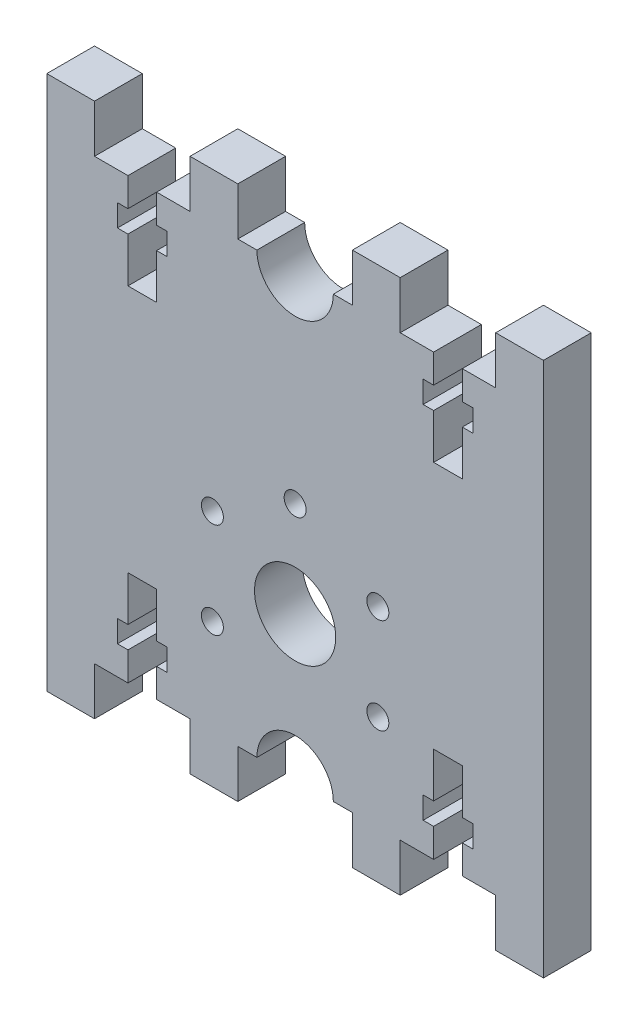
SolidWorks part; units mm, degrees
ref_plane "Front Plane" through (0, 0, 0) normal (0, 0, 1) x (1, 0, 0)
ref_plane "Top Plane" through (0, 0, 0) normal (0, 1, 0) x (1, 0, 0)
ref_plane "Right Plane" through (0, 0, 0) normal (1, 0, 0) x (0, 0, -1)
sketch "Sketch1" plane through (0, 0, 0) normal (0, 0, 1) x (1, 0, 0)
  line L1 (0, 0) -> (20, 0) construction
  line L3 (0, 46) -> (20, 46) construction
  line L8 (10, 46) -> (10, 38.7792) construction
  line L9 (11.5, 46) -> (15, 46)
  line L10 (15, 51) -> (20, 51)
  line L12 (15, 51) -> (15, 46)
  line L13 (8.5, 46) -> (5, 46)
  line L14 (5, 46) -> (5, 51)
  line L15 (5, 51) -> (0, 51)
  line L17 (11.5, 46) -> (8.5, 46) construction
  line L18 (8.5, 46) -> (8.5, 43)
  line L19 (8.5, 40.7) -> (7.4, 40.7)
  line L20 (12.6, 43) -> (12.6, 40.7)
  line L21 (7.4, 43) -> (8.5, 43)
  line L22 (8.5, 40.7) -> (8.5, 36)
  line L23 (8.5, 36) -> (11.5, 36)
  line L24 (11.5, 36) -> (11.5, 40.7)
  line L25 (11.5, 43) -> (12.6, 43)
  line L26 (7.4, 40.7) -> (7.4, 43)
  line L27 (12.6, 40.7) -> (11.5, 40.7)
  line L28 (11.5, 43) -> (11.5, 46)
  line L29 (10, 36) -> (10, 46) construction
  line L30 (10, 0) -> (10, 11.2208) construction
  line L31 (8.5, 0) -> (5, 0)
  line L32 (5, -5) -> (0, -5)
  line L33 (0, -5) -> (0, 0)
  line L34 (5, -5) -> (5, 0)
  line L35 (11.5, 0) -> (15, 0)
  line L36 (15, 0) -> (15, -5)
  line L37 (15, -5) -> (20, -5)
  line L38 (20, -5) -> (20, 0)
  line L39 (8.5, 0) -> (11.5, 0) construction
  line L40 (11.5, 0) -> (11.5, 3)
  line L41 (11.5, 5.3) -> (12.6, 5.3)
  line L42 (7.4, 3) -> (7.4, 5.3)
  line L43 (12.6, 3) -> (11.5, 3)
  line L44 (11.5, 5.3) -> (11.5, 10)
  line L45 (11.5, 10) -> (8.5, 10)
  line L46 (8.5, 10) -> (8.5, 5.3)
  line L47 (8.5, 3) -> (7.4, 3)
  line L48 (12.6, 5.3) -> (12.6, 3)
  line L49 (7.4, 5.3) -> (8.5, 5.3)
  line L50 (8.5, 3) -> (8.5, 0)
  line L51 (10, 10) -> (10, 0) construction
  line L52 (0, 51) -> (0, 0)
  line L54 (20, 51) -> (20, 46)
  line L55 (20, 46) -> (32, 46) construction
  line L56 (20, 0) -> (32, 0) construction
  line L57 (26, 36) -> (26, 0) construction
  line L58 (32, 51) -> (32, 46)
  line L59 (37, 51) -> (32, 51)
  line L60 (37, 51) -> (37, 46)
  line L61 (40.5, 46) -> (37, 46)
  line L62 (40.5, 43) -> (40.5, 46)
  line L63 (40.5, 43) -> (39.4, 43)
  line L64 (39.4, 43) -> (39.4, 40.7)
  line L65 (39.4, 40.7) -> (40.5, 40.7)
  line L66 (40.5, 36) -> (40.5, 40.7)
  line L67 (43.5, 36) -> (40.5, 36)
  line L68 (43.5, 40.7) -> (43.5, 36)
  line L69 (43.5, 40.7) -> (44.6, 40.7)
  line L70 (44.6, 40.7) -> (44.6, 43)
  line L71 (44.6, 43) -> (43.5, 43)
  line L72 (43.5, 46) -> (43.5, 43)
  line L73 (43.5, 46) -> (47, 46)
  line L74 (47, 46) -> (47, 51)
  line L75 (47, 51) -> (52, 51)
  line L76 (52, 51) -> (52, 0)
  line L77 (52, -5) -> (52, 0)
  line L78 (47, -5) -> (52, -5)
  line L79 (47, -5) -> (47, 0)
  line L80 (43.5, 0) -> (47, 0)
  line L81 (43.5, 3) -> (43.5, 0)
  line L82 (43.5, 3) -> (44.6, 3)
  line L83 (44.6, 3) -> (44.6, 5.3)
  line L84 (44.6, 5.3) -> (43.5, 5.3)
  line L85 (43.5, 10) -> (43.5, 5.3)
  line L86 (40.5, 10) -> (43.5, 10)
  line L87 (40.5, 5.3) -> (40.5, 10)
  line L88 (40.5, 5.3) -> (39.4, 5.3)
  line L89 (39.4, 5.3) -> (39.4, 3)
  line L90 (39.4, 3) -> (40.5, 3)
  line L91 (40.5, 0) -> (40.5, 3)
  line L92 (40.5, 0) -> (37, 0)
  line L93 (37, 0) -> (37, -5)
  line L94 (37, -5) -> (32, -5)
  line L95 (32, -5) -> (32, 0)
  line L96 (20, 46) -> (22, 46)
  line L97 (32, 46) -> (30, 46)
  line L99 (20, 0) -> (22, 0)
  line L100 (32, 0) -> (30, 0)
  circle A0 centre (26, 15) radius 4.25
  circle A1 centre (26, 25) radius 1.15
  circle A2 centre (34.6603, 20) radius 1.15
  circle A3 centre (34.6603, 10) radius 1.15
  circle A4 centre (26, 5) radius 1.15 construction
  circle A5 centre (17.3397, 10) radius 1.15
  circle A6 centre (17.3397, 20) radius 1.15
  arc A8 (22, 46) -> (30, 46) centre (26, 46) ccw
  arc A9 (22, 0) -> (30, 0) centre (26, 0) cw
  point P11 (10, 0)
  point P107 (26, 15)
  dimension "D20" = 8.5
  dimension "D21" = 2.3
  dimension "D25" = 4
  dimension "D2" = 46
  dimension "D3" = 10
  dimension "D4" = 5
  dimension "D5" = 5
  dimension "D6" = 5.2
  dimension "D7" = 3
  dimension "D8" = 2.3
  dimension "D9" = 3
  dimension "D10" = 10
  dimension "D11" = 10
  dimension "D12" = 5
  dimension "D13" = 5
  dimension "D14" = 5.2
  dimension "D15" = 3
  dimension "D16" = 2.3
  dimension "D17" = 3
  dimension "D18" = 10
  dimension "D19" = 16
  dimension "D22" = 10
  dimension "D23" = 15
  dimension "D24" = 6
extrude "Boss-Extrude1" add sketch "Sketch1" along normal blind 5
